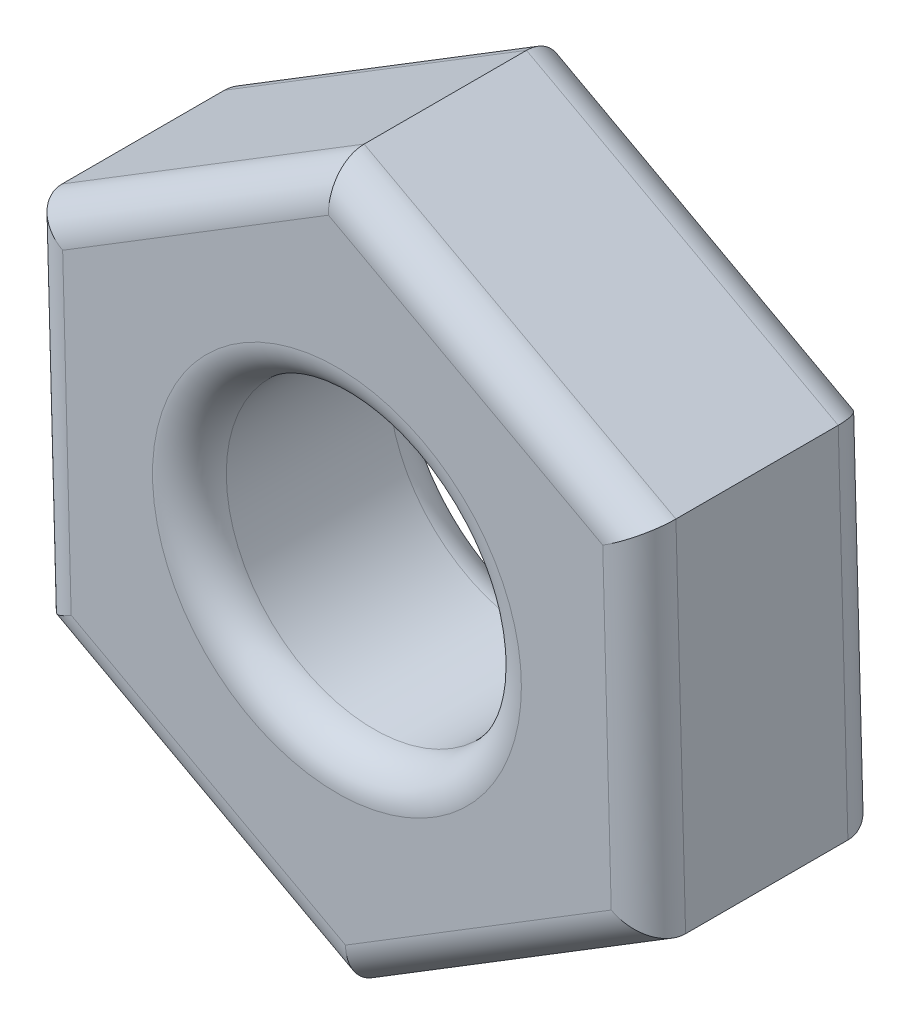
SolidWorks part; units mm, degrees
ref_plane "Front Plane" through (0, 0, 0) normal (0, 0, 1) x (1, 0, 0)
ref_plane "Top Plane" through (0, 0, 0) normal (0, 1, 0) x (1, 0, 0)
ref_plane "Right Plane" through (0, 0, 0) normal (1, 0, 0) x (0, 0, -1)
sketch "Sketch1" plane through (0, 0, 0) normal (0, 0, 1) x (1, 0, 0)
  line L1 (-2.0472, -1.2577) -> (0.0656, -2.4018)
  line L2 (0.0656, -2.4018) -> (2.1128, -1.1441)
  line L3 (2.1128, -1.1441) -> (2.0472, 1.2577)
  line L4 (2.0472, 1.2577) -> (-0.0656, 2.4018)
  line L5 (-0.0656, 2.4018) -> (-2.1128, 1.1441)
  line L6 (-2.1128, 1.1441) -> (-2.0472, -1.2577)
  circle A0 centre (0, 0) radius 1
  circle A1 centre (0, 0) radius 2.0808 construction
  dimension "D1" = 2
  dimension "D2" = 4.16
extrude "Boss-Extrude1" add sketch "Sketch1" along normal blind 1.6
fillet "Fillet1" radius 0.25 14 edges at (1, 0, 0) (-0.9908, -1.8297, 0) (1.0892, -1.7729, 0) (2.08, 0.0568, 0) (0.9908, 1.8297, 0) (-1.0892, 1.7729, 0) (-2.08, -0.0568, 0) (1, 0, 1.6) (-1.0892, 1.7729, 1.6) (0.9908, 1.8297, 1.6) (2.08, 0.0568, 1.6) (1.0892, -1.7729, 1.6) (-0.9908, -1.8297, 1.6) (-2.08, -0.0568, 1.6)
